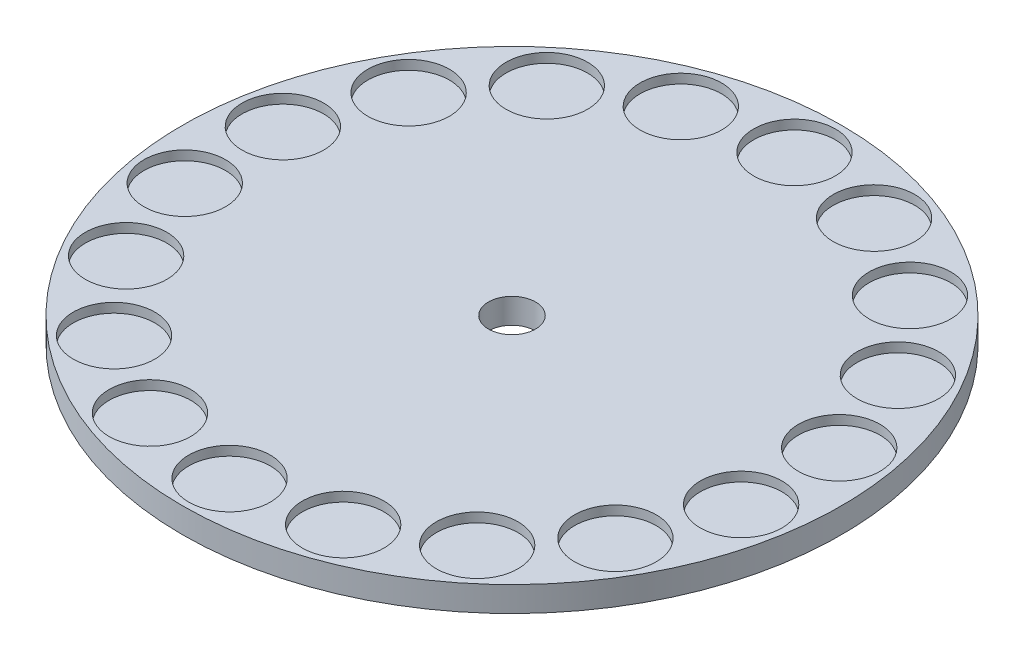
SolidWorks part; units mm, degrees
material "ABS"
ref_plane "Front Plane" through (0, 0, 0) normal (0, 0, 1) x (1, 0, 0)
ref_plane "Top Plane" through (0, 0, 0) normal (0, 1, 0) x (1, 0, 0)
ref_plane "Right Plane" through (0, 0, 0) normal (1, 0, 0) x (0, 0, -1)
sketch "Sketch1" plane through (0, 0, 0) normal (0, 1, 0) x (1, 0, 0)
  circle A12 centre (0, 0) radius 105
  circle A13 centre (0, 0) radius 7.5
  dimension "D1" = 210
  dimension "D2" = 15
sketch "Sketch2" plane through (0, 0, 0) normal (0, 1, 0) x (1, 0, 0)
  line L0 (0, 111.3654) -> (0, -153.9587) construction
  circle A1 centre (0, 0) radius 45 construction
  circle A2 centre (0, 0) radius 105
  circle A13 centre (0, 0) radius 7.5
  circle A16 centre (0, 90) radius 13
  circle A17 centre (30.7818, 84.5723) radius 13
  circle A18 centre (57.8509, 68.944) radius 13
  circle A19 centre (77.9423, 45) radius 13
  circle A20 centre (88.6327, 15.6283) radius 13
  circle A21 centre (88.6327, -15.6283) radius 13
  circle A48 centre (77.9423, -45) radius 13
  circle A49 centre (57.8509, -68.944) radius 13
  circle A50 centre (30.7818, -84.5723) radius 13
  circle A51 centre (0, -90) radius 13
  circle A52 centre (-30.7818, -84.5723) radius 13
  circle A53 centre (-57.8509, -68.944) radius 13
  circle A54 centre (-77.9423, -45) radius 13
  circle A55 centre (-88.6327, -15.6283) radius 13
  circle A56 centre (-88.6327, 15.6283) radius 13
  circle A57 centre (-77.9423, 45) radius 13
  circle A58 centre (-57.8509, 68.944) radius 13
  circle A59 centre (-30.7818, 84.5723) radius 13
  circle A60 centre (0, 0) radius 90 construction
  point P3 (0, 7.5)
  point P27 (0, 0)
  point P29 (0, 0)
  point P77 (0, 0)
  dimension "D2" = 90
  dimension "D4" = 15
  dimension "D5" = 210
  dimension "D7" = 26
  dimension "D6" = 180
  dimension "D9" = 18
extrude "Boss-Extrude1" add sketch "Sketch2" against normal mid plane 8
extrude "Boss-Extrude2" add sketch "Sketch1" along normal mid plane 2
